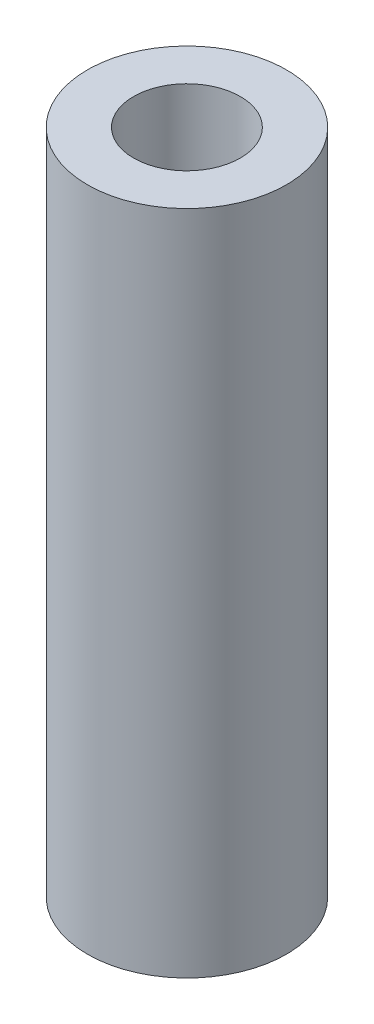
SolidWorks part; units mm, degrees
material "PET"
ref_plane "Front Plane" through (0, 0, 0) normal (0, 0, 1) x (1, 0, 0)
ref_plane "Top Plane" through (0, 0, 0) normal (0, 1, 0) x (1, 0, 0)
ref_plane "Right Plane" through (0, 0, 0) normal (1, 0, 0) x (0, 0, -1)
sketch "Sketch1" plane through (0, 0, 0) normal (0, 1, 0) x (1, 0, 0)
  circle A0 centre (0, 0) radius 2.5527
  circle A1 centre (0, 0) radius 4.7625
  dimension "D1" = 5.1054
  dimension "D2" = 9.525
extrude "Boss-Extrude1" add sketch "Sketch1" along normal blind 31.877
